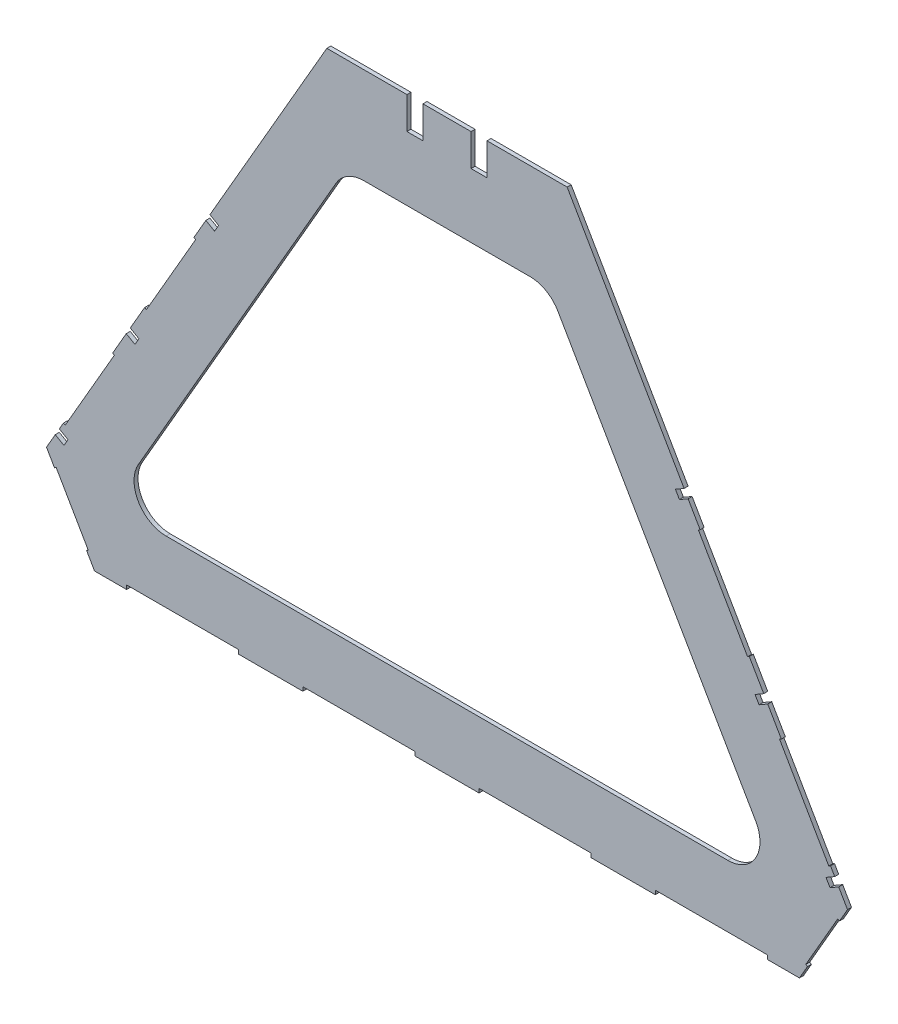
SolidWorks part; units mm, degrees
material "Teak"
ref_plane "Front Plane" through (0, 0, 0) normal (0, 0, 1) x (1, 0, 0)
ref_plane "Top Plane" through (0, 0, 0) normal (0, 1, 0) x (1, 0, 0)
ref_plane "Right Plane" through (0, 0, 0) normal (1, 0, 0) x (0, 0, -1)
sketch "Sketch1" plane through (0, 0, 0) normal (0, 0, 1) x (1, 0, 0)
  line L0 (0, 0) -> (190.5, 0)
  line L1 (190.5, 0) -> (412.75, -384.9483)
  line L2 (412.75, -384.9483) -> (374.65, -450.9394)
  line L3 (374.65, -450.9394) -> (-184.15, -450.9394)
  line L4 (-184.15, -450.9394) -> (-222.25, -384.9483)
  line L5 (-222.25, -384.9483) -> (0, 0)
  dimension "D1" = 444.5
  dimension "D2" = 558.8
  dimension "D3" = 76.2
  dimension "D4" = 76.2
  dimension "D5" = 60
  dimension "D6" = 60
  dimension "D7" = 120
  dimension "D8" = 120
extrude "Boss-Extrude1" add sketch "Sketch1" along normal blind 3.175
sketch "Sketch2" plane through (0, 0, 3.175) normal (0, 0, 1) x (1, 0, 0)
  line L0 (190.5, 0) -> (0, 0) construction
  line L1 (63.5, 0) -> (76.2, 0)
  line L2 (63.5, 0) -> (63.5, -25.4)
  line L3 (63.5, -25.4) -> (76.2, -25.4)
  line L4 (76.2, 0) -> (76.2, -25.4)
  line L5 (29.3294, -76.2) -> (161.1706, -76.2)
  line L6 (114.3, 0) -> (127, 0)
  line L7 (114.3, 0) -> (114.3, -25.4)
  line L8 (114.3, -25.4) -> (127, -25.4)
  line L9 (127, 0) -> (127, -25.4)
  line L10 (183.1677, -88.9) -> (339.953, -360.4601)
  line L11 (317.9559, -398.5601) -> (-127.4559, -398.5601)
  line L12 (-149.453, -360.4601) -> (7.3323, -88.9)
  line L13 (0, 0) -> (-222.25, -384.9483) construction
  line L14 (412.75, -384.9483) -> (190.5, 0) construction
  arc A0 (161.1706, -76.2) -> (183.1677, -88.9) centre (161.1706, -101.6) cw
  arc A1 (29.3294, -76.2) -> (7.3323, -88.9) centre (29.3294, -101.6) ccw
  arc A2 (339.953, -360.4601) -> (317.9559, -398.5601) centre (317.9559, -373.1601) cw
  arc A3 (-127.4559, -398.5601) -> (-149.453, -360.4601) centre (-127.4559, -373.1601) cw
  point P26 (361.95, -398.5601)
  point P29 (-171.45, -398.5601)
  dimension "D11" = 25.4
  dimension "D1" = 63.5
  dimension "D2" = 63.5
  dimension "D3" = 12.7
  dimension "D4" = 25.4
  dimension "D5" = 25.4
  dimension "D6" = 12.7
  dimension "D7" = 50.8
  dimension "D8" = 50.8
  dimension "D9" = 76.2
  dimension "D10" = 533.4
extrude "Cut-Extrude1" cut sketch "Sketch2" against normal through all
sketch "Sketch4" plane through (0, 0, 3.175) normal (0, 0, 1) x (1, 0, 0)
  line L0 (-184.15, -450.9394) -> (374.65, -450.9394) construction
  line L1 (-158.75, -450.9394) -> (-69.85, -450.9394)
  line L2 (-158.75, -450.9394) -> (-158.75, -447.7644)
  line L3 (-158.75, -447.7644) -> (-69.85, -447.7644)
  line L4 (-69.85, -450.9394) -> (-69.85, -447.7644)
  line L5 (-19.05, -447.7644) -> (69.85, -447.7644)
  line L6 (-19.05, -450.9394) -> (-19.05, -447.7644)
  line L7 (-19.05, -450.9394) -> (69.85, -450.9394)
  line L8 (69.85, -450.9394) -> (69.85, -447.7644)
  line L9 (120.65, -447.7644) -> (209.55, -447.7644)
  line L10 (120.65, -450.9394) -> (120.65, -447.7644)
  line L11 (120.65, -450.9394) -> (209.55, -450.9394)
  line L12 (209.55, -450.9394) -> (209.55, -447.7644)
  line L13 (260.35, -447.7644) -> (349.25, -447.7644)
  line L14 (260.35, -450.9394) -> (260.35, -447.7644)
  line L15 (260.35, -450.9394) -> (349.25, -450.9394)
  line L16 (349.25, -450.9394) -> (349.25, -447.7644)
  line L17 (-215.9, -395.9468) -> (-214.5252, -395.1531)
  line L18 (-222.25, -384.9483) -> (-184.15, -450.9394) construction
  line L19 (-214.5252, -395.1531) -> (-189.1252, -439.1472)
  line L20 (-189.1252, -439.1472) -> (-190.5, -439.9409)
  line L21 (-215.9, -395.9468) -> (-190.5, -439.9409)
  line L22 (406.4, -395.9468) -> (405.0252, -395.1531)
  line L23 (374.65, -450.9394) -> (412.75, -384.9483) construction
  line L24 (405.0252, -395.1531) -> (379.6252, -439.1472)
  line L25 (379.6252, -439.1472) -> (381, -439.9409)
  line L26 (381, -439.9409) -> (406.4, -395.9468)
  line L37 (95.25, -1000) -> (95.25, 49000) construction
  line L38 (114.3, 0) -> (76.2, 0) construction
  point P7 (-69.85, -449.3519)
  point P51 (95.25, 0)
  dimension "D1" = 25.4
  dimension "D2" = 88.9
  dimension "D3" = 3.175
  dimension "D4" = 4
  dimension "D5" = 50.8
  dimension "D6" = 12.7
  dimension "D7" = 1.5875
  dimension "D8" = 12.7
  dimension "D9" = 50.8
  dimension "D10" = 1.5875
  dimension "D11" = 12.7
  dimension "D12" = 12.7
extrude "Cut-Extrude2" cut sketch "Sketch4" against normal through all
sketch "Sketch5" plane through (0, 0, 3.175) normal (0, 0, 1) x (1, 0, 0)
  line L0 (-208.788, -361.6314) -> (-207.4132, -362.4252)
  line L1 (0, 0) -> (-222.25, -384.9483) construction
  line L2 (-207.4132, -362.4252) -> (-168.4242, -294.8942)
  line L3 (-168.4242, -294.8942) -> (-169.799, -294.1005)
  line L4 (-169.799, -294.1005) -> (-208.788, -361.6314)
  line L5 (-143.0242, -250.9002) -> (-104.0352, -183.3692)
  line L6 (-105.41, -182.5755) -> (-144.399, -250.1064)
  line L7 (-144.399, -250.1064) -> (-143.0242, -250.9002)
  line L8 (-104.0352, -183.3692) -> (-105.41, -182.5755)
  line L9 (95.25, -1000) -> (95.25, 49000) construction
  line L10 (114.3, 0) -> (76.2, 0) construction
  line L11 (399.288, -361.6314) -> (397.9132, -362.4252)
  line L12 (358.9242, -294.8942) -> (360.299, -294.1005)
  line L13 (360.299, -294.1005) -> (399.288, -361.6314)
  line L14 (397.9132, -362.4252) -> (358.9242, -294.8942)
  line L15 (334.899, -250.1064) -> (333.5242, -250.9002)
  line L16 (294.5352, -183.3692) -> (295.91, -182.5755)
  line L17 (295.91, -182.5755) -> (334.899, -250.1064)
  line L18 (333.5242, -250.9002) -> (294.5352, -183.3692)
  point P6 (-169.1116, -294.4974)
  point P17 (95.25, 0)
  dimension "D1" = 26.924
  dimension "D2" = 77.978
  dimension "D3" = 1.5875
  dimension "D5" = 50.8
  dimension "D4" = 2
extrude "Cut-Extrude3" cut sketch "Sketch5" against normal through all
sketch "Sketch6" plane through (0, 0, 3.175) normal (0, 0, 1) x (1, 0, 0)
  line L1 (-144.399, -250.1064) -> (-169.799, -294.1005) construction
  line L2 (-155.829, -269.9037) -> (-148.9549, -273.8725)
  line L3 (-148.9549, -273.8725) -> (-152.1299, -279.3718)
  line L4 (-152.1299, -279.3718) -> (-159.004, -275.403)
  line L6 (-159.004, -275.403) -> (-155.829, -269.9037)
  line L7 (-168.4242, -294.8942) -> (-169.799, -294.1005) construction
  line L8 (95.25, -1000) -> (95.25, 49000) construction
  line L9 (114.3, 0) -> (76.2, 0) construction
  line L10 (349.504, -275.403) -> (346.329, -269.9037)
  line L11 (342.6299, -279.3718) -> (349.504, -275.403)
  line L12 (339.4549, -273.8725) -> (342.6299, -279.3718)
  line L13 (346.329, -269.9037) -> (339.4549, -273.8725)
  line L14 (-205.2159, -371.3194) -> (-208.3909, -376.8187)
  line L15 (-208.3909, -376.8187) -> (-215.265, -372.8499)
  line L16 (-212.09, -367.3507) -> (-205.2159, -371.3194)
  line L17 (-215.265, -372.8499) -> (-212.09, -367.3507)
  line L18 (-85.8359, -164.5472) -> (-89.0109, -170.0464)
  line L19 (-89.0109, -170.0464) -> (-95.885, -166.0777)
  line L20 (-92.71, -160.5784) -> (-85.8359, -164.5472)
  line L21 (-95.885, -166.0777) -> (-92.71, -160.5784)
  line L22 (-104.0352, -183.3692) -> (-105.41, -182.5755) construction
  line L23 (286.385, -166.0777) -> (283.21, -160.5784)
  line L24 (283.21, -160.5784) -> (276.3359, -164.5472)
  line L25 (279.5109, -170.0464) -> (286.385, -166.0777)
  line L26 (276.3359, -164.5472) -> (279.5109, -170.0464)
  line L27 (405.765, -372.8499) -> (402.59, -367.3507)
  line L28 (402.59, -367.3507) -> (395.7159, -371.3194)
  line L29 (398.8909, -376.8187) -> (405.765, -372.8499)
  line L30 (395.7159, -371.3194) -> (398.8909, -376.8187)
  point P15 (95.25, 0)
  dimension "D1" = 6.35
  dimension "D2" = 7.9375
  dimension "D3" = 21.59
  dimension "D5" = 13.97
  dimension "D7" = 19.05
  dimension "D4" = 2
  dimension "D6" = 2
extrude "Cut-Extrude4" cut sketch "Sketch6" against normal through all
sketch "Sketch7" plane through (0, 0, 3.175) normal (0, 0, 1) x (1, 0, 0)
  line L0 (114.3, 0) -> (76.2, 0) construction
  line L1 (63.5, 0) -> (0, 0) construction
  circle A0 centre (31.75, -38.1) radius 6.35
  circle A1 centre (158.75, -38.1) radius 6.35
  point P6 (95.25, 0)
  dimension "D1" = 12.7
  dimension "D2" = 63.5
  dimension "D3" = 127
  dimension "D4" = 38.1
extrude "Cut-Extrude5" [suppressed] cut sketch "Sketch7" against normal through all
